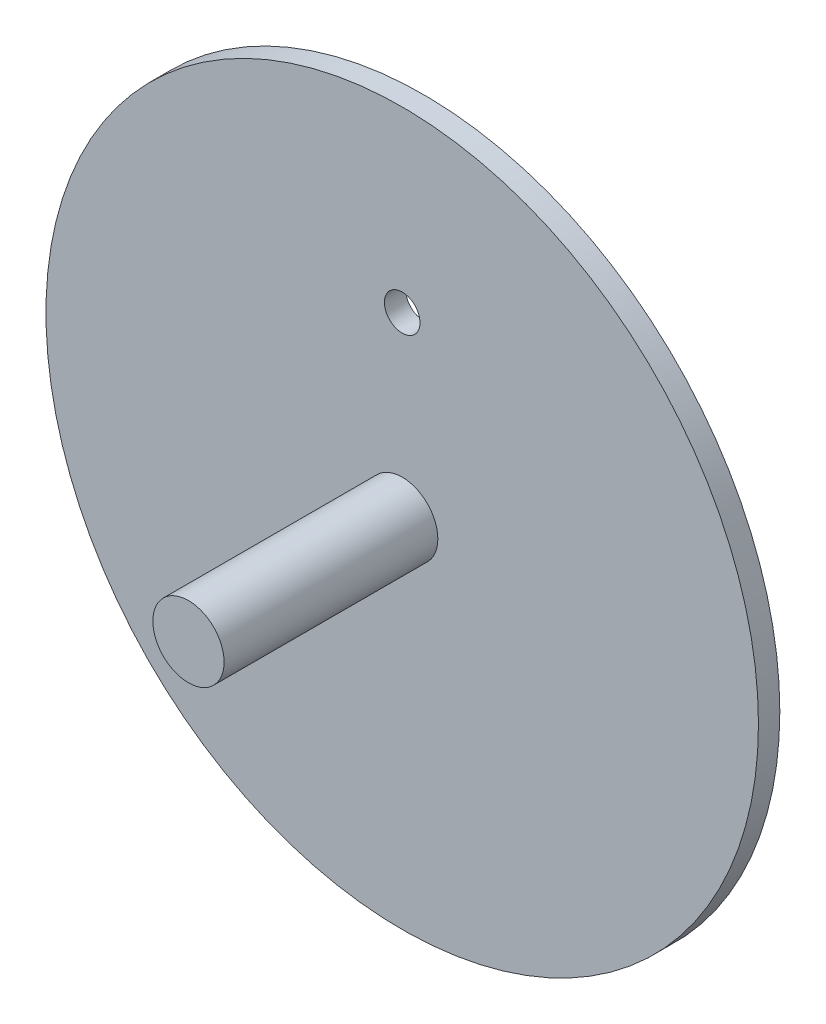
SolidWorks part; units mm, degrees
ref_plane "Спереди" through (0, 0, 0) normal (0, 0, 1) x (1, 0, 0)
ref_plane "Сверху" through (0, 0, 0) normal (0, 1, 0) x (1, 0, 0)
ref_plane "Справа" through (0, 0, 0) normal (1, 0, 0) x (0, 0, -1)
sketch "Эскиз1" plane through (0, 0, 0) normal (0, 0, 1) x (1, 0, 0)
  circle A0 centre (0, 0) radius 50
  dimension "D1" = 100
extrude "Бобышка-Вытянуть1" add sketch "Эскиз1" along normal blind 3
sketch "Эскиз2" plane through (0, 0, 3) normal (0, 0, 1) x (1, 0, 0)
  circle A0 centre (0, 0) radius 5
  dimension "D1" = 10
extrude "Бобышка-Вытянуть2" add sketch "Эскиз2" along normal blind 30
sketch "Эскиз3" plane through (0, 0, 3) normal (0, 0, 1) x (1, 0, 0)
  circle A0 centre (0, 25) radius 2.5
  dimension "D1" = 5
  dimension "D2" = 25
extrude "Вырез-Вытянуть1" cut sketch "Эскиз3" against normal through all
